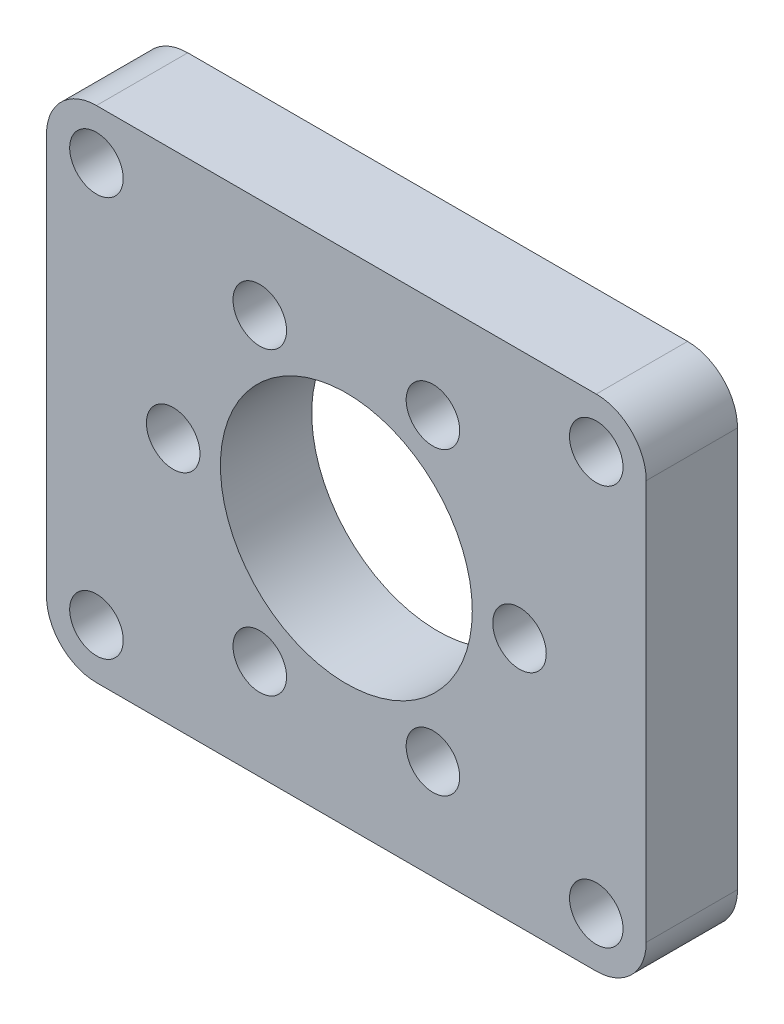
SolidWorks part; units mm, degrees
material "Acrylic (Medium-high impact)"
ref_plane "Front" through (0, 0, 0) normal (0, 0, 1) x (1, 0, 0)
ref_plane "Top" through (0, 0, 0) normal (0, 1, 0) x (1, 0, 0)
ref_plane "Right" through (0, 0, 0) normal (1, 0, 0) x (0, 0, -1)
sketch "Sketch1" plane through (0, 0, 0) normal (0, 0, 1) x (1, 0, 0)
  line L0 (0, 15.875) -> (19.05, 15.875) construction
  line L1 (0, 0) -> (38.1, 0)
  line L2 (0, 0) -> (0, 31.75)
  line L3 (0, 31.75) -> (38.1, 31.75)
  line L4 (38.1, 0) -> (38.1, 31.75)
  line L5 (19.05, 15.875) -> (19.05, 31.75) construction
  dimension "D1" = 38.1
  dimension "D2" = 31.75
extrude "Boss-Extrude1" add sketch "Sketch1" along normal blind 5.8
sketch "Sketch2" plane through (0, 0, 5.8) normal (0, 0, 1) x (1, 0, 0)
  line L0 (0, 15.875) -> (38.1, 15.875) construction
  line L1 (0, 31.75) -> (0, 0) construction
  line L2 (38.1, 0) -> (38.1, 31.75) construction
  line L3 (19.05, 31.75) -> (19.05, 0) construction
  line L4 (38.1, 31.75) -> (0, 31.75) construction
  line L5 (0, 0) -> (38.1, 0) construction
  circle A0 centre (19.05, 15.875) radius 8
  dimension "D1" = 16
extrude "Cut-Extrude1" cut sketch "Sketch2" against normal through all
hole_wizard "M3 Clearance Hole1" positions "Sketch4" profile "Sketch3" hole size "M3" standard "Ansi Metric"
sketch "Sketch4" plane through (0, 0, 5.8) normal (0, 0, 1) x (1, 0, 0)
  line L0 (19.05, 15.875) -> (30.05, 15.875) construction
  line L1 (19.05, 15.875) -> (24.55, 25.4013) construction
  line L2 (19.05, 15.875) -> (13.55, 25.4013) construction
  line L3 (19.05, 15.875) -> (8.05, 15.875) construction
  line L4 (19.05, 15.875) -> (13.55, 6.3487) construction
  line L5 (19.05, 15.875) -> (24.55, 6.3487) construction
  point P0 (30.05, 15.875)
  point P9 (24.55, 25.4013)
  point P12 (13.55, 25.4013)
  point P15 (8.05, 15.875)
  point P18 (13.55, 6.3487)
  point P21 (24.55, 6.3487)
  dimension "D1" = 11
  dimension "D2" = 6
sketch "Sketch3" plane through (30.05, 15.875, 5.8) normal (1, 0, 0) x (0, -1, 0)
  line L0 (0, 0) -> (0, 7.3715)
  line L1 (0, 7.3715) -> (1.7, 6.35)
  line L2 (1.7, 6.35) -> (1.7, 0)
  line L5 (1.7, 0) -> (0, 0)
  line L10 (0, 7.3715) -> (-1.7, 6.35) construction
  line L11 (0, -6.35) -> (0, 107.95) construction
  dimension "Hole Dia." = 3.4
  dimension "Hole Depth" = 6.35
  dimension "Drill Angle" = 118
hole_wizard "M3 Clearance Hole2" positions "Sketch6" profile "Sketch5" hole size "M3" standard "Ansi Metric"
sketch "Sketch6" plane through (0, 0, 5.8) normal (0, 0, 1) x (1, 0, 0)
  line L0 (19.05, 15.875) -> (19.05, 31.75) construction
  line L1 (38.1, 31.75) -> (0, 31.75) construction
  line L3 (19.05, 15.875) -> (0, 15.875) construction
  line L4 (0, 31.75) -> (0, 0) construction
  line L6 (3.175, 28.575) -> (3.175, 15.875) construction
  point P0 (3.175, 28.575)
  point P18 (34.925, 28.575)
  point P20 (34.925, 3.175)
  point P21 (3.175, 3.175)
  dimension "D1" = 3.175
  dimension "D2" = 3.175
sketch "Sketch5" plane through (3.175, 28.575, 5.8) normal (1, 0, 0) x (0, -1, 0)
  line L0 (0, 0) -> (0, 7.3715)
  line L1 (0, 7.3715) -> (1.7, 6.35)
  line L2 (1.7, 6.35) -> (1.7, 0)
  line L5 (1.7, 0) -> (0, 0)
  line L10 (0, 7.3715) -> (-1.7, 6.35) construction
  line L11 (0, -6.35) -> (0, 107.95) construction
  dimension "Hole Dia." = 3.4
  dimension "Hole Depth" = 6.35
  dimension "Drill Angle" = 118
fillet "Fillet1" radius 3.175 4 edges at (0, 0, 2.9) (0, 31.75, 2.9) (38.1, 31.75, 2.9) (38.1, 0, 2.9)
other "Move Face1" [suppressed] parameters "D1"=0.2
